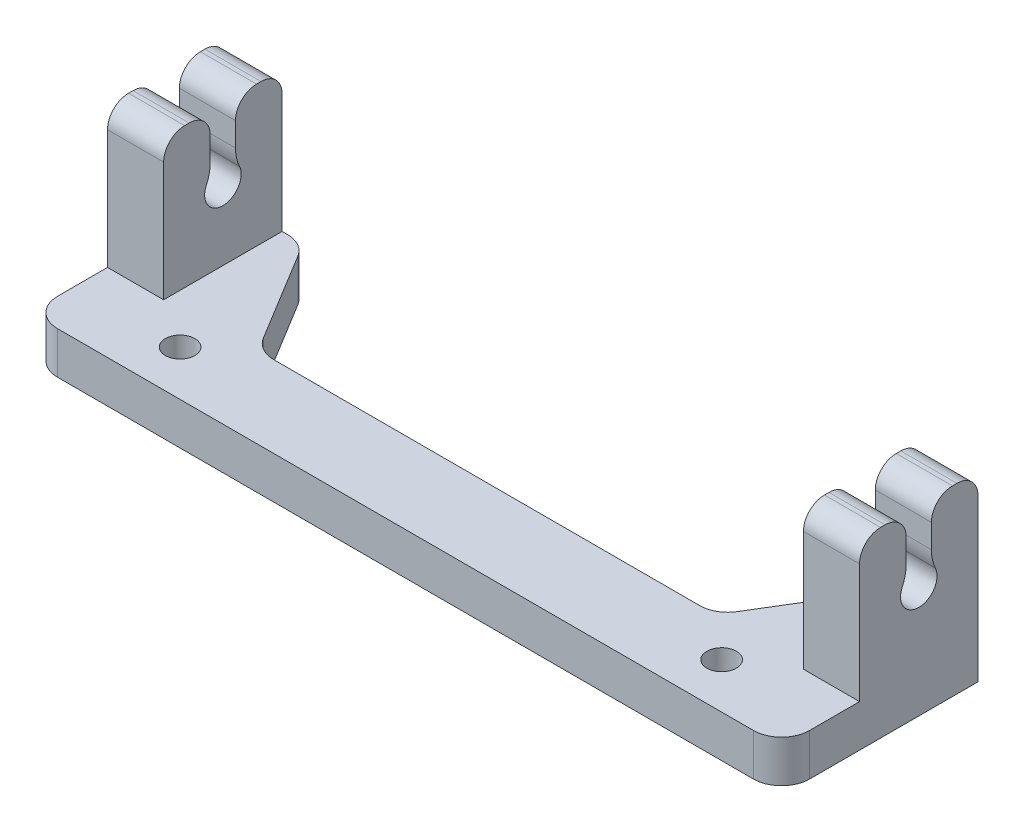
SolidWorks part; units mm, degrees
ref_plane "Front Plane" through (0, 0, 0) normal (0, 0, 1) x (1, 0, 0)
ref_plane "Top Plane" through (0, 0, 0) normal (0, 1, 0) x (1, 0, 0)
ref_plane "Right Plane" through (0, 0, 0) normal (1, 0, 0) x (0, 0, -1)
sketch "Sketch1" plane through (0, 0, 0) normal (0, 1, 0) x (1, 0, 0)
  line L0 (0, 0) -> (24.458, 0)
  line L1 (26.458, 2) -> (26.458, 14)
  line L2 (26.458, 14) -> (22.0817, 14)
  line L3 (20.3735, 13.0403) -> (16.5425, 6.7497)
  line L4 (14.8343, 5.79) -> (-15.5083, 5.79)
  line L5 (-17.2165, 6.7497) -> (-21.0475, 13.0403)
  line L6 (-22.7557, 14) -> (-27.132, 14)
  line L7 (-27.132, 14) -> (-27.132, 2)
  line L8 (-25.132, 0) -> (0, 0)
  circle A0 centre (18.958, 3.23) radius 1.05
  circle A1 centre (-19.632, 3.23) radius 1.05
  arc A2 (16.5425, 6.7497) -> (14.8343, 5.79) centre (14.8343, 7.79) cw
  arc A3 (-15.5083, 5.79) -> (-17.2165, 6.7497) centre (-15.5083, 7.79) cw
  arc A4 (-21.0475, 13.0403) -> (-22.7557, 14) centre (-22.7557, 12) ccw
  arc A5 (22.0817, 14) -> (20.3735, 13.0403) centre (22.0817, 12) ccw
  arc A6 (24.458, 0) -> (26.458, 2) centre (24.458, 2) ccw
  arc A7 (-27.132, 2) -> (-25.132, 0) centre (-25.132, 2) ccw
  point P14 (0, 0)
  point P15 (0, 0)
  point P16 (0, 0)
  point P19 (15.958, 5.79)
  point P22 (-16.632, 5.79)
  point P25 (-21.632, 14)
  point P28 (20.958, 14)
  point P31 (26.458, 0)
  dimension "D2" = 2.1
  dimension "D3" = 2.1
  dimension "D13" = 2
  dimension "D1" = 38.59
  dimension "D4" = 3.23
  dimension "D5" = 5.79
  dimension "D6" = 14
  dimension "D7" = 7.5
  dimension "D8" = 3
  dimension "D9" = 3
  dimension "D10" = 2
  dimension "D11" = 2
  dimension "D12" = 7.5
extrude "Boss-Extrude1" add sketch "Sketch1" along normal blind 3
sketch "Sketch2" plane through (0, 3, 0) normal (0, 1, 0) x (1, 0, 0)
  line L1 (-27.132, 14) -> (-23.132, 14)
  line L2 (-27.132, 14) -> (-27.132, 5.56)
  line L3 (-27.132, 5.56) -> (-23.132, 5.56)
  line L4 (-23.132, 14) -> (-23.132, 5.56)
  line L5 (26.458, 14) -> (22.458, 14)
  line L6 (26.458, 14) -> (26.458, 5.56)
  line L7 (26.458, 5.56) -> (22.458, 5.56)
  line L8 (22.458, 14) -> (22.458, 5.56)
  dimension "D1" = 4
  dimension "D2" = 4
  dimension "D3" = 8.44
extrude "Boss-Extrude2" add sketch "Sketch2" along normal blind 10
sketch "Sketch3" plane through (26.458, 0, 0) normal (1, 0, 0) x (0, 0, -1)
  line L0 (14, 13) -> (14, 0) construction
  line L1 (2, 0) -> (14, 0) construction
  line L2 (8.88, 13) -> (8.88, 8.9381)
  line L3 (5.56, 13) -> (14, 13) construction
  line L4 (10.68, 13) -> (10.68, 8.9381)
  circle A0 centre (9.78, 8) radius 1.3
  line M5 (14, 13) -> (5.56, 13)
  dimension "D1" = 2.6
  dimension "D2" = 4.22
  dimension "D3" = 8
  dimension "D4" = 0.9
  dimension "D5" = 0.9
extrude "Cut-Extrude1" cut sketch "Sketch3" against normal through all contours A0 L4 L2 M5 | A0
fillet "Fillet1" radius 3 4 edges at (24.458, 8.9381, -8.88) (-25.132, 8.9381, -8.88) (-25.132, 8.9381, -10.68) (24.458, 8.9381, -10.68)
fillet "Fillet6" radius 1.5 8 edges at (-25.132, 13, -5.56) (-25.132, 13, -14) (24.458, 13, -14) (24.458, 13, -5.56) (24.458, 13, -10.68) (24.458, 13, -8.88) (-25.132, 13, -10.68) (-25.132, 13, -8.88)
